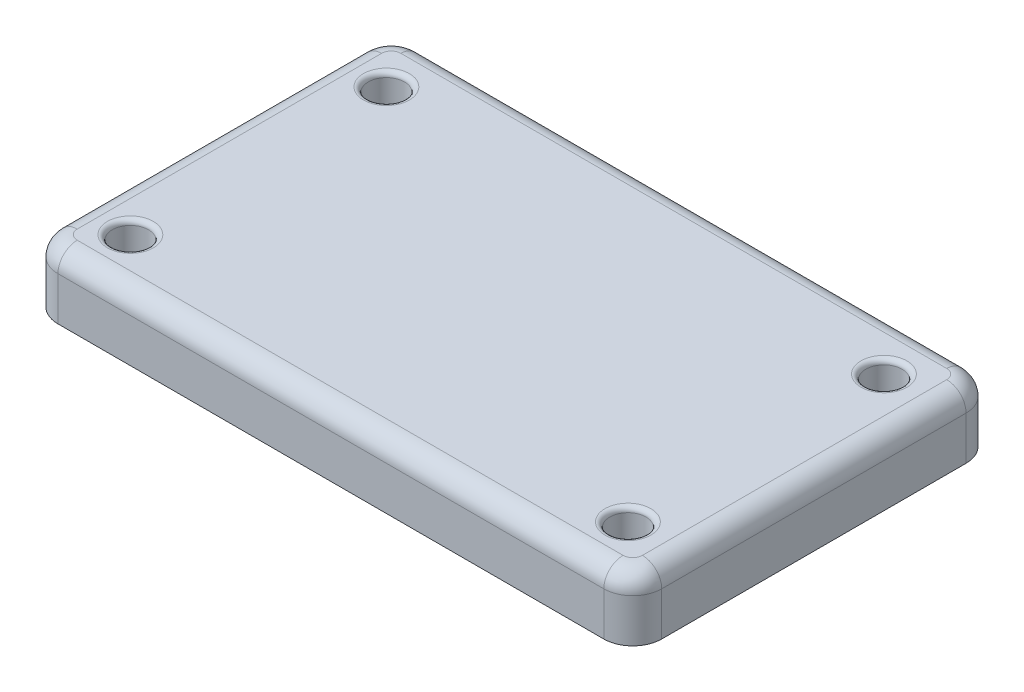
SolidWorks part; units mm, degrees
ref_plane "Front Plane" through (0, 0, 0) normal (0, 0, 1) x (1, 0, 0)
ref_plane "Top Plane" through (0, 0, 0) normal (0, 1, 0) x (1, 0, 0)
ref_plane "Right Plane" through (0, 0, 0) normal (1, 0, 0) x (0, 0, -1)
sketch "Sketch1" plane through (0, 0, 0) normal (0, 1, 0) x (1, 0, 0)
  line L1 (-56.5, 37.5) -> (56.5, 37.5)
  line L2 (-62.5, 31.5) -> (-62.5, -31.5)
  line L3 (-56.5, -37.5) -> (56.5, -37.5)
  line L4 (62.5, 31.5) -> (62.5, -31.5)
  line L5 (-62.5, 37.5) -> (62.5, -37.5) construction
  line L6 (-62.5, -37.5) -> (62.5, 37.5) construction
  arc A0 (-62.5, -31.5) -> (-56.5, -37.5) centre (-56.5, -31.5) ccw
  arc A1 (56.5, -37.5) -> (62.5, -31.5) centre (56.5, -31.5) ccw
  arc A2 (56.5, 37.5) -> (62.5, 31.5) centre (56.5, 31.5) cw
  arc A3 (-56.5, 37.5) -> (-62.5, 31.5) centre (-56.5, 31.5) ccw
  point P0 (0, 0)
  dimension "D3" = 6
  dimension "D1" = 125
  dimension "D2" = 75
extrude "Boss-Extrude1" add sketch "Sketch1" along normal blind 13
sketch "Sketch2" plane through (0, 0, 0) normal (0, -1, 0) x (1, 0, 0)
  line L0 (-56.5, -35.5) -> (56.5, -35.5)
  line L1 (60.5, -31.5) -> (60.5, 31.5)
  line L2 (56.5, 35.5) -> (-56.5, 35.5)
  line L3 (-60.5, 31.5) -> (-60.5, -31.5)
  line L4 (-62.5, 31.5) -> (-62.5, -31.5)
  line L5 (-56.5, -37.5) -> (56.5, -37.5)
  line L6 (62.5, -31.5) -> (62.5, 31.5)
  line L7 (56.5, 37.5) -> (-56.5, 37.5)
  line L8 (-62.5, 31.5) -> (-62.5, -31.5)
  line L9 (-56.5, -37.5) -> (56.5, -37.5)
  line L10 (62.5, -31.5) -> (62.5, 31.5)
  line L11 (56.5, 37.5) -> (-56.5, 37.5)
  arc A0 (56.5, -35.5) -> (60.5, -31.5) centre (56.5, -31.5) ccw
  arc A1 (60.5, 31.5) -> (56.5, 35.5) centre (56.5, 31.5) ccw
  arc A2 (-56.5, 35.5) -> (-60.5, 31.5) centre (-56.5, 31.5) ccw
  arc A3 (-60.5, -31.5) -> (-56.5, -35.5) centre (-56.5, -31.5) ccw
  arc A4 (-56.5, 37.5) -> (-62.5, 31.5) centre (-56.5, 31.5) ccw
  arc A5 (-62.5, -31.5) -> (-56.5, -37.5) centre (-56.5, -31.5) ccw
  arc A6 (56.5, -37.5) -> (62.5, -31.5) centre (56.5, -31.5) ccw
  arc A7 (62.5, 31.5) -> (56.5, 37.5) centre (56.5, 31.5) ccw
  arc A8 (-56.5, 37.5) -> (-62.5, 31.5) centre (-56.5, 31.5) ccw
  arc A9 (-62.5, -31.5) -> (-56.5, -37.5) centre (-56.5, -31.5) ccw
  arc A10 (56.5, -37.5) -> (62.5, -31.5) centre (56.5, -31.5) ccw
  arc A11 (62.5, 31.5) -> (56.5, 37.5) centre (56.5, 31.5) ccw
  dimension "D1" = 0
  dimension "D2" = 2
extrude "Cut-Extrude1" cut sketch "Sketch2" against normal blind 11 contours L3 A3 L0 A0 L1 A1 L2 A2
sketch "Sketch3" plane through (0, 13, 0) normal (0, 1, 0) x (1, 0, 0)
  circle A0 centre (-52, -27) radius 1.35 construction
  circle A1 centre (-52, -27) radius 1.35
  circle A2 centre (51, -27) radius 1.35 construction
  circle A3 centre (51, -27) radius 1.35
  circle A4 centre (51, 26) radius 1.35 construction
  circle A5 centre (-52, 26) radius 1.35 construction
  circle A6 centre (51, 26) radius 1.35
  circle A7 centre (-52, 26) radius 1.35
extrude "Cut-Extrude2" cut sketch "Sketch3" against normal through all
sketch "Sketch4" plane through (0, 13, 0) normal (0, 1, 0) x (1, 0, 0)
  circle A0 centre (-52, 26) radius 3.75
  circle A1 centre (-52, 26) radius 1.35 construction
  circle A2 centre (-52, -27) radius 3.75
  circle A3 centre (-52, -27) radius 1.35 construction
  circle A4 centre (51, -27) radius 3.75
  circle A5 centre (51, -27) radius 1.35 construction
  circle A6 centre (51, 26) radius 3.75
  circle A7 centre (51, 26) radius 1.35 construction
  dimension "D1" = 7.5
sketch "Sketch5" plane through (0, 11, 0) normal (0, -1, 0) x (1, 0, 0)
  line L0 (55.25, 27) -> (55.25, -26)
  line L1 (60.5, 0) -> (53.75, 0) construction
  line L2 (60.5, -31.5) -> (60.5, 31.5) construction
  line L3 (47.7596, 29.75) -> (-48.7596, 29.75)
  line L4 (-52, -21.75) -> (-52, -26) construction
  line L5 (-52, -26) -> (-52, 27) construction
  line L6 (51, -26) -> (51, 27) construction
  line L7 (51, -30.25) -> (-52, -30.25)
  line L8 (47.7596, -28.75) -> (-48.7596, -28.75)
  line L9 (53.75, 23.7596) -> (53.75, -22.7596)
  line L10 (-52, 27) -> (-52, 22.75) construction
  line L11 (-52, 0.5) -> (51, 0.5) construction
  line L12 (-52, -12.8812) -> (0, -12.8812) construction
  line L13 (0, -12.8812) -> (0, 17.6787) construction
  line L14 (51, 31.25) -> (-52, 31.25)
  line L15 (-0.5, -30.25) -> (-0.5, 23.7596) construction
  line L16 (-56.25, 27) -> (-56.25, -26)
  line L17 (-54.75, 23.7596) -> (-54.75, -22.7596)
  circle A0 centre (-52, -26) radius 4.25
  circle A1 centre (-52, -26) radius 1.35 construction
  circle A2 centre (-52, 27) radius 4.25
  circle A3 centre (-52, 27) radius 1.35 construction
  circle A4 centre (51, -26) radius 4.25
  circle A5 centre (51, -26) radius 1.35 construction
  circle A6 centre (51, 27) radius 4.25
  circle A7 centre (51, 27) radius 1.35 construction
  circle A8 centre (-52, 27) radius 1.35
  circle A9 centre (-52, -26) radius 1.35
  circle A10 centre (51, 27) radius 1.35
  circle A11 centre (51, -26) radius 1.35
  circle M9 centre (-52, -26) radius 1.35
  circle M10 centre (51, -26) radius 1.35
  circle M11 centre (51, 27) radius 1.35
  circle M12 centre (-52, 27) radius 1.35
  dimension "D1" = 8.5
  dimension "D2" = 1.5
  dimension "D3" = 1.5
extrude "Boss-Extrude2" add sketch "Sketch5" along normal blind 10 contours A4 L8 A0 L7 | A0 M9 | A2 L16 A0 L17 | A2 M12 | A6 L14 A2 L3 | A4 M10 | A6 L9 A4 L0 | A6 M11
sketch "Sketch6" plane through (0, 13, 0) normal (0, 1, 0) x (1, 0, 0)
  circle A0 centre (51, 26) radius 3.75 construction
  circle A1 centre (51, -27) radius 3.75 construction
  circle A2 centre (-52, 26) radius 3.75 construction
  circle A3 centre (-52, -27) radius 3.75 construction
  circle A4 centre (51, 26) radius 3.75
  circle A5 centre (51, -27) radius 3.75
  circle A6 centre (-52, 26) radius 3.75
  circle A7 centre (-52, -27) radius 3.75
extrude "Cut-Extrude3" cut sketch "Sketch6" against normal blind 6.6
fillet "Fillet1" radius 1 4 edges at (51, 13, -22.25) (51, 13, 30.75) (-52, 13, -22.25) (-52, 13, 30.75)
fillet "Fillet2" radius 4 8 edges at (0, 13, -37.5) (60.7426, 13, -35.7426) (62.5, 13, 0) (60.7426, 13, 35.7426) (0, 13, 37.5) (-60.7426, 13, 35.7426) (-62.5, 13, 0) (-60.7426, 13, -35.7426)
sketch "Sketch7" plane through (0, 13, 0) normal (0, 1, 0) x (1, 0, 0)
  line L0 (0, 0) -> (62.5, 0) construction
  line L2 (24.5, 13.75) -> (39.5, 13.75)
  line L3 (24.5, 13.75) -> (24.5, -13.75)
  line L4 (24.5, -13.75) -> (39.5, -13.75)
  line L5 (39.5, 13.75) -> (39.5, -13.75)
  line L6 (24.5, 13.75) -> (39.5, -13.75) construction
  line L7 (24.5, -13.75) -> (39.5, 13.75) construction
  line L8 (62.5, 31.5) -> (62.5, -31.5) construction
  line L9 (0, 0) -> (-62.5, 0) construction
  line L10 (-62.5, -31.5) -> (-62.5, 31.5) construction
  point P3 (31.25, 0)
  point P12 (32, 0)
  dimension "D1" = 23
  dimension "D2" = 27.5
  dimension "D3" = 15
sketch "Sketch8" plane through (0, 11, 0) normal (0, -1, 0) x (1, 0, 0)
  line L4 (-60.5, 31.5) -> (-60.5, -31.5)
  line L5 (-56.5, -35.5) -> (56.5, -35.5)
  line L6 (60.5, -31.5) -> (60.5, 31.5)
  line L7 (56.5, 35.5) -> (-56.5, 35.5)
  line L8 (-60.5, 31.5) -> (-60.5, -31.5)
  line L9 (-56.5, -35.5) -> (56.5, -35.5)
  line L10 (60.5, -31.5) -> (60.5, 31.5)
  line L11 (56.5, 35.5) -> (-56.5, 35.5)
  line L13 (55.25, 27) -> (55.25, -26) construction
  line L14 (51, -30.25) -> (-52, -30.25) construction
  line L15 (55.25, 27) -> (55.25, -26)
  line L16 (51, -30.25) -> (-52, -30.25)
  line L17 (-56.25, 27) -> (-56.25, -26) construction
  line L18 (-56.25, 27) -> (-56.25, -26)
  line L19 (51, 31.25) -> (-52, 31.25) construction
  line L20 (51, 31.25) -> (-52, 31.25)
  arc A4 (-60.5, -31.5) -> (-56.5, -35.5) centre (-56.5, -31.5) ccw
  arc A5 (56.5, -35.5) -> (60.5, -31.5) centre (56.5, -31.5) ccw
  arc A6 (60.5, 31.5) -> (56.5, 35.5) centre (56.5, 31.5) ccw
  arc A7 (-56.5, 35.5) -> (-60.5, 31.5) centre (-56.5, 31.5) ccw
  arc A8 (-60.5, -31.5) -> (-56.5, -35.5) centre (-56.5, -31.5) ccw
  arc A9 (56.5, -35.5) -> (60.5, -31.5) centre (56.5, -31.5) ccw
  arc A10 (60.5, 31.5) -> (56.5, 35.5) centre (56.5, 31.5) ccw
  arc A11 (-56.5, 35.5) -> (-60.5, 31.5) centre (-56.5, 31.5) ccw
  arc A13 (51, -30.25) -> (55.25, -26) centre (51, -26) ccw construction
  arc A14 (51, -30.25) -> (55.25, -26) centre (51, -26) ccw
  arc A15 (-56.25, -26) -> (-52, -30.25) centre (-52, -26) ccw construction
  arc A16 (-56.25, -26) -> (-52, -30.25) centre (-52, -26) ccw
  arc A17 (55.25, 27) -> (51, 31.25) centre (51, 27) ccw construction
  arc A18 (-52, 31.25) -> (-56.25, 27) centre (-52, 27) ccw construction
  arc A19 (55.25, 27) -> (51, 31.25) centre (51, 27) ccw
  arc A20 (-52, 31.25) -> (-56.25, 27) centre (-52, 27) ccw
  dimension "D1" = 0
extrude "Boss-Extrude4" add sketch "Sketch8" along normal blind 2.5
